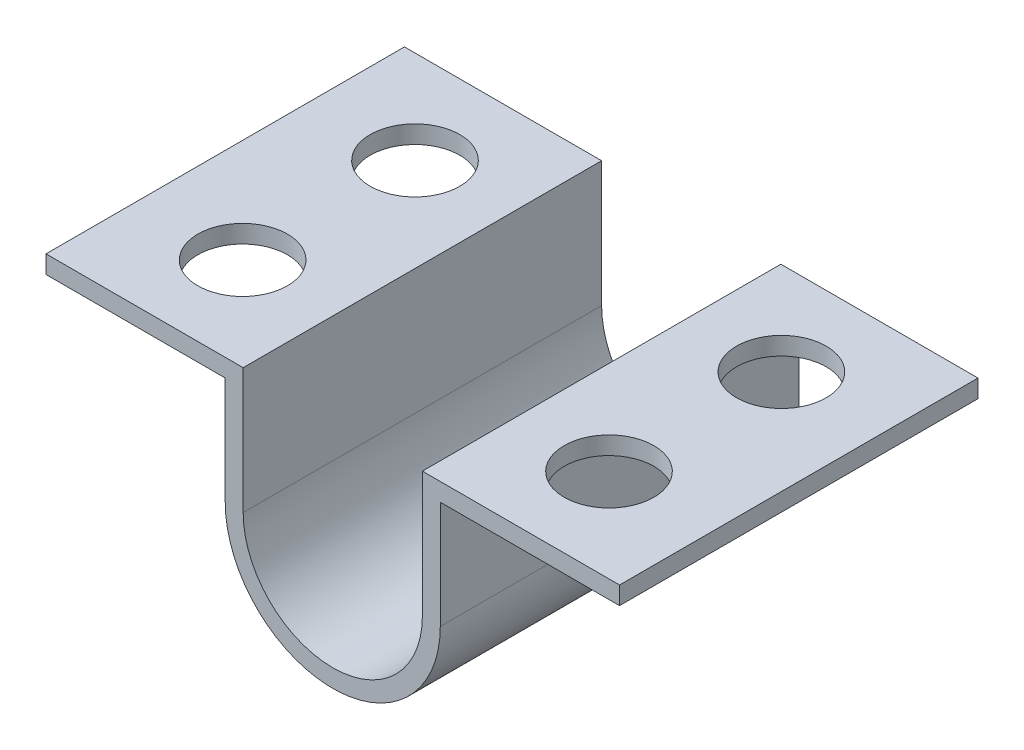
SolidWorks part; units mm, degrees
ref_plane "Front Plane" through (0, 0, 0) normal (0, 0, 1) x (1, 0, 0)
ref_plane "Top Plane" through (0, 0, 0) normal (0, 1, 0) x (1, 0, 0)
ref_plane "Right Plane" through (0, 0, 0) normal (1, 0, 0) x (0, 0, -1)
sketch "Sketch1" plane through (0, 0, 0) normal (0, 0, 1) x (1, 0, 0)
  line L0 (0, 0) -> (-5, 0)
  line L1 (-5, 0) -> (-5, -3)
  line L2 (-11, -3) -> (-11, 0)
  line L3 (-11, 0) -> (-16, 0)
  arc A0 (-5, -3) -> (-11, -3) centre (-8, -3) cw
  dimension "D1" = 3
  dimension "D2" = 5
  dimension "D3" = 5
  dimension "D4" = 3
  dimension "D5" = 3
extrude "Extrude-Thin4" add sketch "Sketch1" along normal blind 10 thin
sketch "Sketch2" plane through (0, 0, 0) normal (0, 1, 0) x (1, 0, 0)
  circle A0 centre (-13.1104, -2.5958) radius 1.25
  dimension "D1" = 2.5
extrude "Cut-Extrude1" cut sketch "Sketch2" along normal through all
ref_plane "Plane1" through (0, 0, 5) normal (0, 0, 1) x (1, 0, 0)
mirror "Mirror1" about plane through (0, 0, 5) normal (0, 0, 1) of "Cut-Extrude1"
ref_plane "Plane2" through (-8, 0, 0) normal (1, 0, 0) x (0, 0, -1)
mirror "Mirror2" about plane through (-8, 0, 0) normal (1, 0, 0) of "Mirror1", "Cut-Extrude1"
